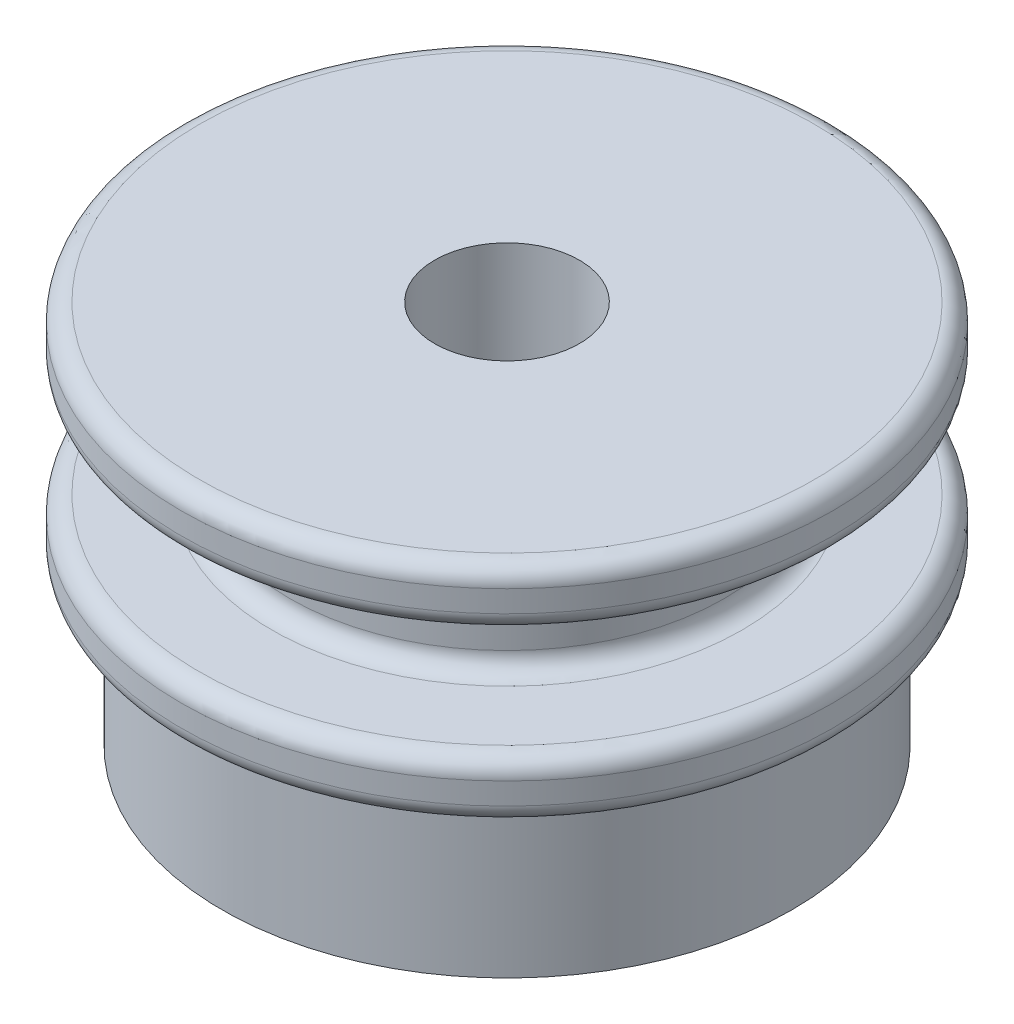
SolidWorks part; units mm, degrees
ref_plane "Front Plane" through (0, 0, 0) normal (0, 0, 1) x (1, 0, 0)
ref_plane "Top Plane" through (0, 0, 0) normal (0, 1, 0) x (1, 0, 0)
ref_plane "Right Plane" through (0, 0, 0) normal (1, 0, 0) x (0, 0, -1)
sketch "Sketch2" plane through (0, 0, 0) normal (0, 0, 1) x (1, 0, 0)
  line L0 (0, 0) -> (9.525, 0) construction
  line L2 (0, 4.9213) -> (14.2875, 4.9213)
  line L3 (14.2875, 4.9213) -> (14.2875, 2.3812)
  line L4 (14.2875, 2.3812) -> (9.525, 2.3812)
  line L5 (9.525, 2.3812) -> (9.525, -2.3813)
  line L6 (9.525, -2.3813) -> (14.2875, -2.3813)
  line L7 (14.2875, -2.3813) -> (14.2875, -4.9212)
  line L8 (14.2875, -4.9212) -> (0, -4.9213)
  line L9 (0, -4.9213) -> (0, 4.9213)
  point P1 (0, 0)
  point P14 (55.7542, 9.1653)
  point P15 (63.5561, -9.2632)
  point P16 (59.3861, 1.767)
  point P17 (9.525, 0)
  point P18 (3.7659, 4.4786)
  dimension "D1" = 4.7625
  dimension "D2" = 4.7625
  dimension "D3" = 14.2875
  dimension "D4" = 2.54
revolve "Revolve1" add sketch "Sketch2" angle 360 about L9
fillet "Fillet1" radius 0.7937 6 edges at (9.525, -2.3813, 0) (9.525, 2.3812, 0) (14.2875, 4.9213, 0) (14.2875, 2.3812, 0) (14.2875, -4.9212, 0) (14.2875, -2.3813, 0)
sketch "Sketch3" plane through (0, 4.9213, 0) normal (0, 1, 0) x (1, 0, 0)
  circle A1 centre (0, 0) radius 3.175
  dimension "D1" = 6.35
extrude "Cut-Extrude1" cut sketch "Sketch3" against normal blind 6.35
sketch "Sketch6" plane through (0, -4.9213, 0) normal (0, -1, 0) x (1, 0, 0)
  circle A0 centre (0, 0) radius 12.5
  dimension "D1" = 25
extrude "Boss-Extrude1" add sketch "Sketch6" along normal blind 7
sketch "Sketch4" plane through (0, -11.9213, 0) normal (0, 1, 0) x (1, 0, 0)
  circle A0 centre (0, 0) radius 2.0955
  dimension "D1" = 4.191
extrude "Cut-Extrude2" cut sketch "Sketch4" against normal through all and the other way through all
sketch "Sketch5" plane through (0, -11.9213, 0) normal (0, -1, 0) x (1, 0, 0)
  line L0 (-6.35, 0) -> (6.35, 0) construction
  circle A0 centre (-6.35, 0) radius 1.6256
  circle A1 centre (6.35, 0) radius 1.6256
  point P4 (0, 0)
  dimension "D2" = 3.2512
  dimension "D1" = 12.7
extrude "Cut-Extrude3" cut sketch "Sketch5" against normal blind 6.35
